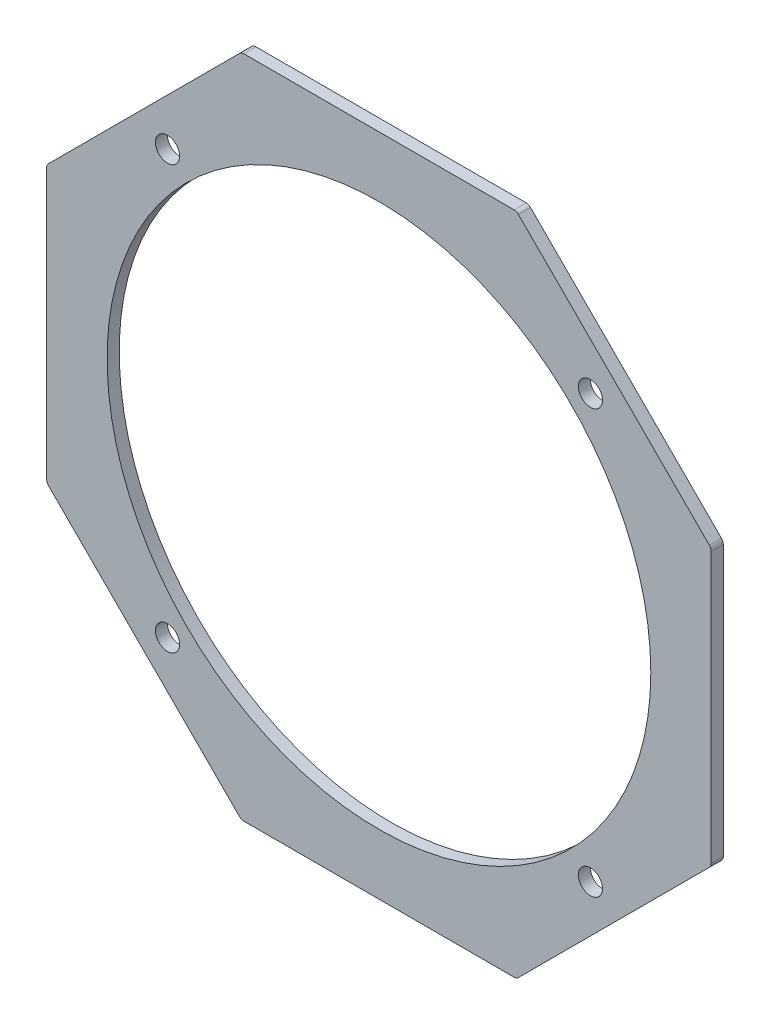
SolidWorks part; units mm, degrees
ref_plane "前视基准面" through (0, 0, 0) normal (0, 0, 1) x (1, 0, 0)
ref_plane "上视基准面" through (0, 0, 0) normal (0, 1, 0) x (1, 0, 0)
ref_plane "右视基准面" through (0, 0, 0) normal (1, 0, 0) x (0, 0, -1)
sketch "Model" plane through (0, 0, 0) normal (0, 0, 1) x (1, 0, 0)
  line L0 (2630.5751, 2001.1966) -> (2598.9426, 1969.5642)
  line L1 (2598.6497, 1968.857) -> (2598.6497, 1924.122)
  line L2 (2598.9426, 1923.4149) -> (2630.5751, 1891.7824)
  line L3 (2631.2822, 1891.4895) -> (2676.0173, 1891.4895)
  line L4 (2676.7244, 1891.7824) -> (2708.3568, 1923.4149)
  line L5 (2708.6497, 1924.122) -> (2708.6497, 1968.857)
  line L6 (2708.3568, 1969.5642) -> (2676.7244, 2001.1966)
  line L7 (2676.0173, 2001.4895) -> (2631.2822, 2001.4895)
  circle A0 centre (2618.6479, 1911.4877) radius 2
  circle A1 centre (2688.6515, 1981.4913) radius 2
  circle A2 centre (2618.6479, 1981.4913) radius 2
  circle A3 centre (2688.6515, 1911.4877) radius 2
  circle A4 centre (2653.6497, 1946.4895) radius 45
  arc A5 (2598.9426, 1969.5642) -> (2598.6497, 1968.857) centre (2599.6497, 1968.857) ccw
  arc A6 (2598.6497, 1924.122) -> (2598.9426, 1923.4149) centre (2599.6497, 1924.122) ccw
  arc A7 (2630.5751, 1891.7824) -> (2631.2822, 1891.4895) centre (2631.2822, 1892.4895) ccw
  arc A8 (2676.0173, 1891.4895) -> (2676.7244, 1891.7824) centre (2676.0173, 1892.4895) ccw
  arc A9 (2708.3568, 1923.4149) -> (2708.6497, 1924.122) centre (2707.6497, 1924.122) ccw
  arc A10 (2708.6497, 1968.857) -> (2708.3568, 1969.5642) centre (2707.6497, 1968.857) ccw
  arc A11 (2676.7244, 2001.1966) -> (2676.0173, 2001.4895) centre (2676.0173, 2000.4895) ccw
  arc A12 (2631.2822, 2001.4895) -> (2630.5751, 2001.1966) centre (2631.2822, 2000.4895) ccw
  spline S0 degree 3 poles (0, 0) (0.3333, 0) (0.6667, 0) (1, 0) knots 0 0 0 0 1 1 1 1
extrude "凸台-拉伸1" add sketch "Model" along normal blind 2 contours L7 A12 L0 A5 L1 A6 L2 A7 L3 A8 L4 A9 L5 A10 L6 A11 A0 A1 A2 A3 A4
